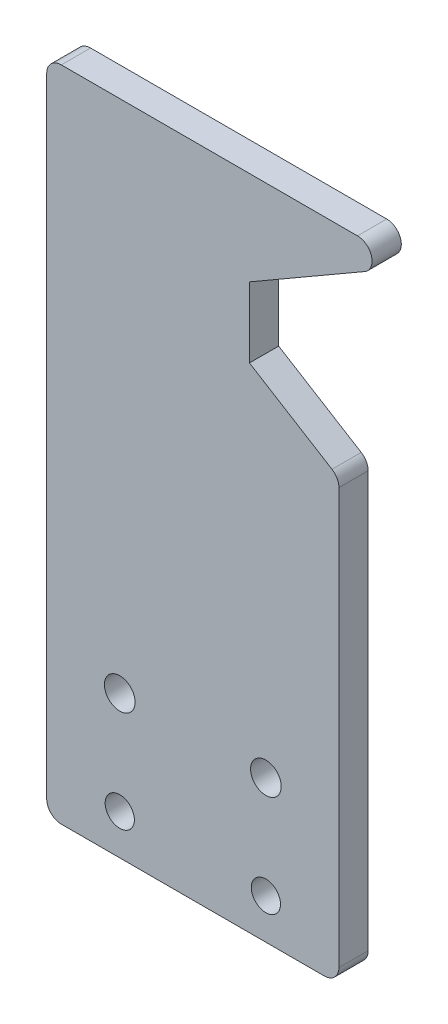
SolidWorks part; units mm, degrees
material "Thornel Mat VMA"
ref_plane "前视基准面" through (0, 0, 0) normal (0, 0, 1) x (1, 0, 0)
ref_plane "上视基准面" through (0, 0, 0) normal (0, 1, 0) x (1, 0, 0)
ref_plane "右视基准面" through (0, 0, 0) normal (1, 0, 0) x (0, 0, -1)
other "Configuration Table"
sketch "草图1" plane through (0, 0, 0) normal (0, 0, 1) x (1, 0, 0)
  line L0 (-20, 60) -> (-20, 30)
  line L2 (-20, 30) -> (-20, -30)
  line L3 (-20, -30) -> (20, -30)
  line L4 (20, 30) -> (20, -30)
  line L5 (-20, 30) -> (20, -30) construction
  line L6 (-20, -30) -> (20, 30) construction
  line L7 (-20, 30) -> (-8.1252, 30)
  line L8 (-20, 60) -> (22.5359, 60)
  line L10 (23.5359, 56.2679) -> (7.7493, 47.1536)
  line L11 (7.7493, 47.1536) -> (7.7493, 37.5408)
  line L12 (7.7493, 37.5408) -> (20, 30)
  arc A0 (22.5359, 60) -> (23.5359, 56.2679) centre (22.5359, 58) cw
  point P0 (0, 0)
  point P19 (30, 60)
  dimension "D7" = 2
  dimension "D1" = 40
  dimension "D2" = 60
  dimension "D3" = 90
  dimension "D4" = 30
  dimension "D5" = 50
  dimension "D6" = 30
extrude "凸台-拉伸1" add sketch "草图1" along normal blind 4
sketch "草图2" plane through (0, 0, 4) normal (0, 0, 1) x (1, 0, 0)
  line L1 (-20, -30) -> (20, -30) construction
  line L2 (0, -30) -> (0, -4.5877) construction
  circle A0 centre (-10, -24.5) radius 2
  circle A1 centre (-10, -10.5) radius 2.1
  circle A2 centre (10, -10.5) radius 2.1
  circle A3 centre (10, -24.5) radius 2
  dimension "D2" = 4
  dimension "D4" = 4.2
  dimension "D1" = 5.5
  dimension "D3" = 20
  dimension "D5" = 14
extrude "切除-拉伸1" cut sketch "草图2" against normal up to next
fillet "圆角1" radius 2 4 edges at (-20, -30, 2) (20, -30, 2) (-20, 60, 2) (20, 30, 2)
